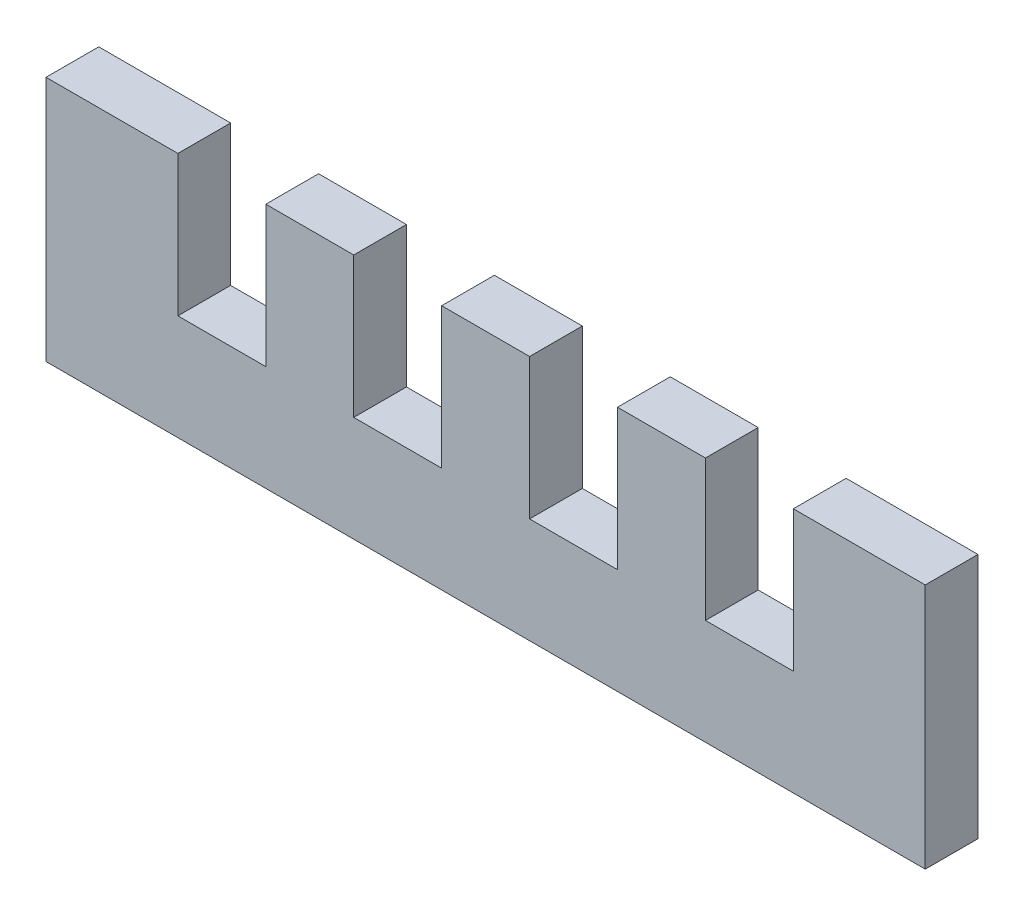
SolidWorks part; units mm, degrees
ref_plane "Front Plane" through (0, 0, 0) normal (0, 0, 1) x (1, 0, 0)
ref_plane "Top Plane" through (0, 0, 0) normal (0, 1, 0) x (1, 0, 0)
ref_plane "Right Plane" through (0, 0, 0) normal (1, 0, 0) x (0, 0, -1)
sketch "Sketch1" plane through (0, 0, 0) normal (0, 0, 1) x (1, 0, 0)
  line L0 (-25, 0) -> (25, 0)
  line L1 (25, 0) -> (25, 14)
  line L2 (-25, 0) -> (-25, 14)
  line L3 (-25, 14) -> (-17.5, 14)
  line L4 (-17.5, 14) -> (-17.5, 6)
  line L5 (-17.5, 6) -> (-12.5, 6)
  line L6 (-12.5, 6) -> (-12.5, 14)
  line L7 (-7.5, 14) -> (-7.5, 6)
  line L8 (-7.5, 6) -> (-2.5, 6)
  line L9 (-12.5, 14) -> (-7.5, 14)
  line L10 (-2.5, 6) -> (-2.5, 14)
  line L11 (-2.5, 14) -> (2.5, 14)
  line L12 (2.5, 14) -> (2.5, 6)
  line L13 (2.5, 6) -> (7.5, 6)
  line L14 (7.5, 6) -> (7.5, 14)
  line L16 (-25, 0) -> (-15, 0)
  line L17 (-15, 0) -> (-15, 14) construction
  line L18 (-5, 0) -> (-5, 14) construction
  line L19 (5, 0) -> (5, 14) construction
  line L20 (15, 0) -> (15, 14) construction
  line L21 (7.5, 14) -> (12.5, 14)
  line L22 (12.5, 14) -> (12.5, 6)
  line L23 (12.5, 6) -> (17.5, 6)
  line L24 (17.5, 6) -> (17.5, 14)
  line L25 (17.5, 14) -> (25, 14)
  point P3 (-15, 6)
  point P4 (0, 0)
  point P27 (-5, 6)
  point P28 (15, 6)
  point P29 (5, 6)
  dimension "D1" = 50
  dimension "D2" = 14
  dimension "D3" = 20
  dimension "D4" = 5
  dimension "D5" = 8
  dimension "D7" = 5
  dimension "D6" = 5
  dimension "D8" = 5
  dimension "D10" = 10
  dimension "D11" = 4
extrude "Boss-Extrude1" add sketch "Sketch1" along normal blind 3 contours L25 L24 L23 L22 L21 L14 L13 L12 L11 L10 L8 L7 L9 L6 L5 L4 L3 L2 L0 L1
